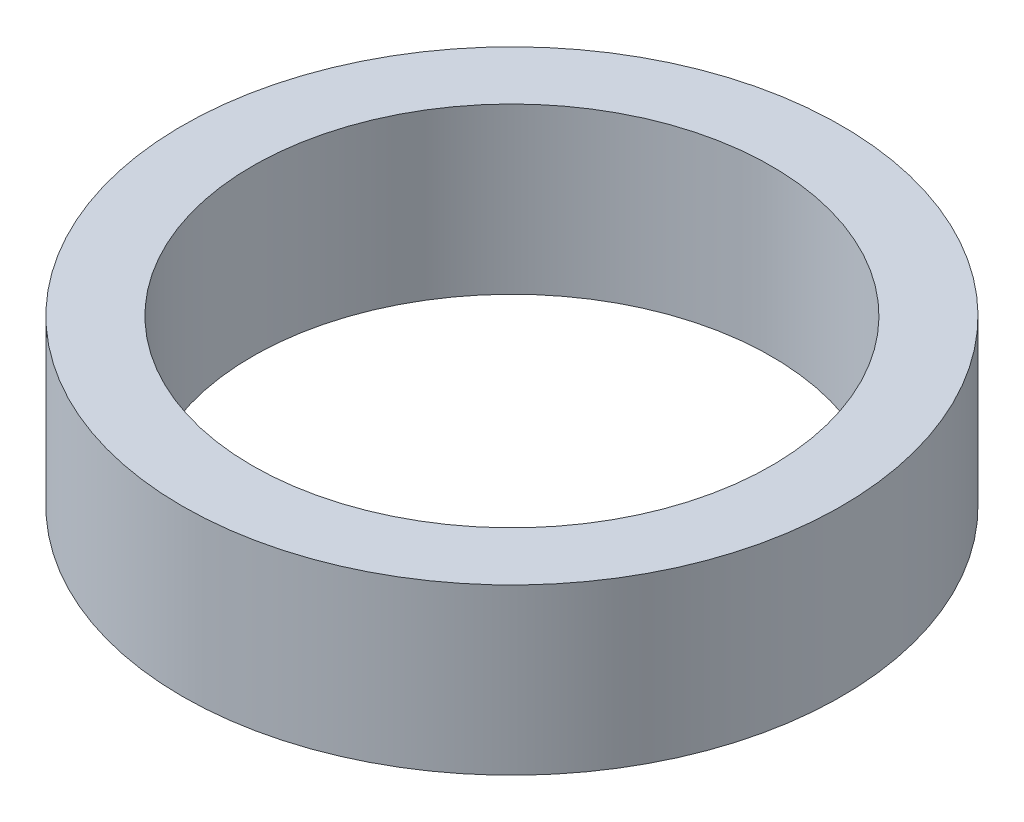
SolidWorks part; units mm, degrees
material "ABS"
ref_plane "Front Plane" through (0, 0, 0) normal (0, 0, 1) x (1, 0, 0)
ref_plane "Top Plane" through (0, 0, 0) normal (0, 1, 0) x (1, 0, 0)
ref_plane "Right Plane" through (0, 0, 0) normal (1, 0, 0) x (0, 0, -1)
sketch "Sketch1" plane through (0, 0, 0) normal (0, 1, 0) x (1, 0, 0)
  circle A0 centre (0, 0) radius 3.15
  circle A1 centre (0, 0) radius 4
  dimension "D1" = 6.3
  dimension "D2" = 8
extrude "Boss-Extrude1" add sketch "Sketch1" along normal blind 2
